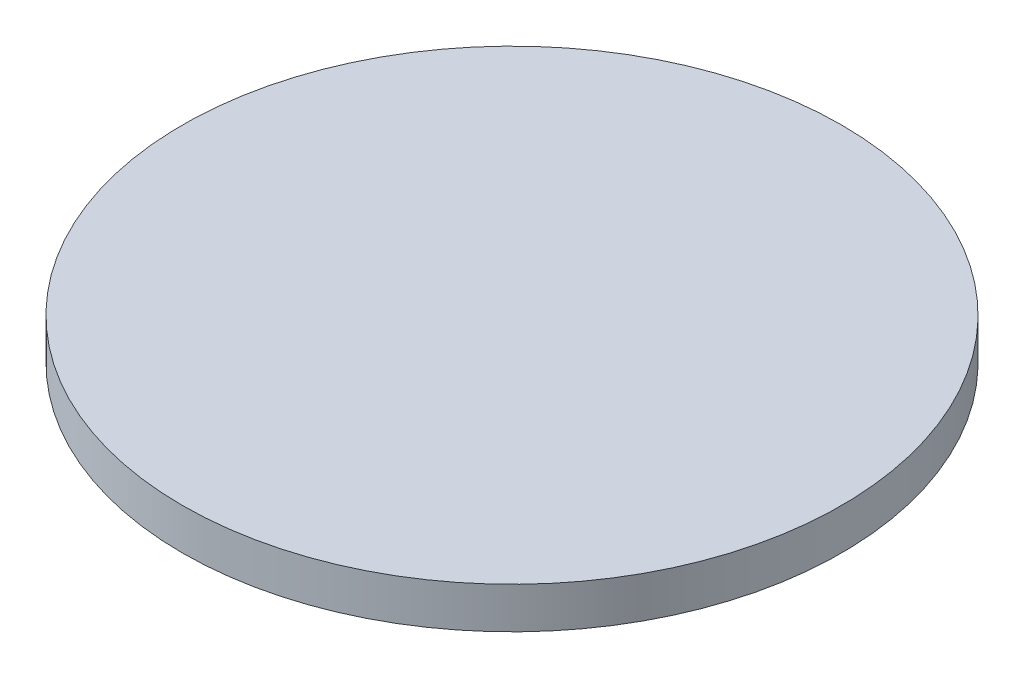
SolidWorks part; units mm, degrees
material "Литая легированная сталь"
ref_plane "Спереди" through (0, 0, 0) normal (0, 0, 1) x (1, 0, 0)
ref_plane "Сверху" through (0, 0, 0) normal (0, 1, 0) x (1, 0, 0)
ref_plane "Справа" through (0, 0, 0) normal (1, 0, 0) x (0, 0, -1)
sketch "Эскиз1" plane through (0, 0, 0) normal (0, 1, 0) x (1, 0, 0)
  circle A0 centre (0, 0) radius 12
  dimension "D1" = 24
extrude "Бобышка-Вытянуть1" add sketch "Эскиз1" along normal blind 1.5
